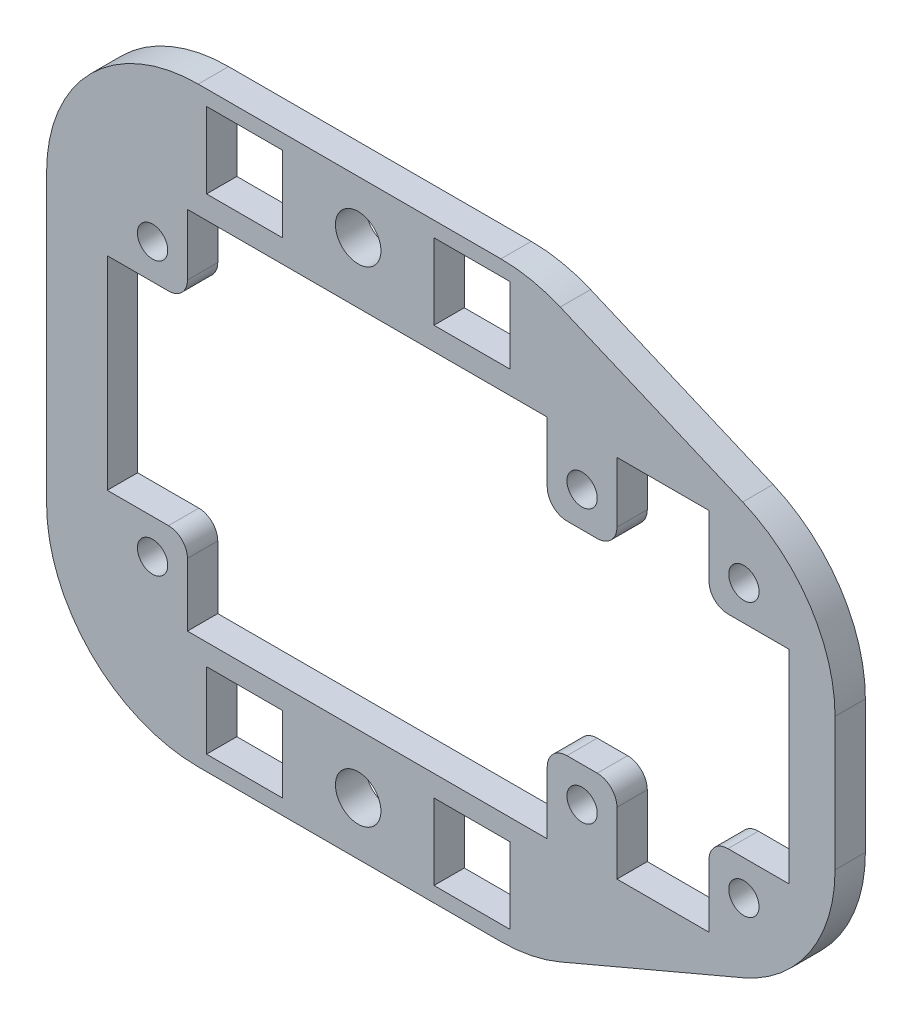
SolidWorks part; units mm, degrees
ref_plane "Plan de face" through (0, 0, 0) normal (0, 0, 1) x (1, 0, 0)
ref_plane "Plan de dessus" through (0, 0, 0) normal (0, 1, 0) x (1, 0, 0)
ref_plane "Plan de droite" through (0, 0, 0) normal (1, 0, 0) x (0, 0, -1)
sketch "Esquisse1" plane through (0, 0, 0) normal (0, 0, 1) x (1, 0, 0)
  line L0 (-4, 19.5) -> (48, 19.5) construction
  line L1 (48, 19.5) -> (48, -19.5) construction
  line L2 (48, -19.5) -> (-4, -19.5) construction
  line L3 (-4, -19.5) -> (-4, 19.5)
  line L4 (0, 0) -> (44.9752, 0) construction
  line L5 (-4, 19.5) -> (28, 19.5)
  line L6 (28, 19.5) -> (48, 11)
  line L7 (48, 11) -> (48, -11)
  line L8 (48, -11) -> (28, -19.5)
  line L9 (28, -19.5) -> (-4, -19.5)
  point P0 (0, 0)
  line B0 (28.5158, -12.1) -> (5.9876, -12.1) construction
  line B1 (0.2864, -6.7) -> (0.2984, -6.7)
  line B2 (5.2876, -7.95) -> (5.2876, -11.5) construction
  line B3 (0.2984, -6.7) -> (4.0376, -6.7) construction
  line B4 (0, -8) -> (0, 8) construction
  line B5 (44.6876, -6.7) -> (40.9376, -6.7) construction
  line B6 (39.6876, -7.95) -> (39.6876, -11.7) construction
  line B7 (44.9752, 8) -> (44.9752, -8) construction
  line B8 (4.0376, 6.7) -> (0, 6.7)
  line B9 (3.9876, 11.9876) -> (40.9876, 11.9876) construction
  line B10 (0, 6.7) -> (0, -6.7)
  line B11 (0, -6.7) -> (4.0376, -6.7)
  line B12 (39.6876, 7.95) -> (39.6876, 11.6999) construction
  line B13 (44.6876, 6.7) -> (40.9376, 6.7) construction
  line B14 (5.2876, -7.95) -> (5.2876, -12.1)
  line B15 (5.2876, -12.1) -> (29.0158, -12.1)
  line B16 (29.0158, -12.1) -> (29.0158, -8)
  line B17 (33.6158, -8) -> (33.6158, -12.1)
  line B18 (33.6158, -12.1) -> (39.6876, -12.1)
  line B19 (39.6876, -12.1) -> (39.6876, -7.95)
  line B20 (40.9376, -6.7) -> (44.9752, -6.7)
  line B21 (44.9752, -6.7) -> (44.9752, 6.7)
  line B22 (44.9752, 6.7) -> (40.9376, 6.7)
  line B23 (39.6876, 7.95) -> (39.6876, 11.9876)
  line B24 (39.6876, 11.9876) -> (33.6158, 11.9876)
  line B25 (33.6158, 11.9876) -> (33.6158, 8)
  line B26 (29.0158, 8) -> (29.0158, 11.9876)
  line B27 (29.0158, 11.9876) -> (5.2876, 11.9876)
  line B28 (5.2876, 11.9876) -> (5.2876, 7.95)
  line B29 (0.2984, 6.7) -> (0.2864, 6.6999)
  line B30 (4.0376, 6.7) -> (0.2984, 6.7) construction
  line B31 (5.2876, 11.4999) -> (5.2876, 7.95) construction
  line B32 (29.0158, 8) -> (29.0158, 11.6999) construction
  line B33 (33.6158, 11.6999) -> (33.6158, 8) construction
  line B34 (32.3158, 6.7) -> (30.3158, 6.7)
  line B35 (33.6158, -8) -> (33.6158, -11.7) construction
  line B36 (30.3158, -6.7) -> (32.3158, -6.7)
  line B37 (29.0158, -11.7) -> (29.0158, -8) construction
  arc B38 (5.2876, -7.95) -> (4.0376, -6.7) centre (4.0376, -7.95) ccw
  arc B39 (40.9376, -6.7) -> (39.6876, -7.95) centre (40.9376, -7.95) ccw
  arc B40 (31.3158, 10) -> (31.3158, 8) centre (31.3158, 9) ccw
  arc B41 (31.3158, 8) -> (31.3158, 10) centre (31.3158, 9) ccw
  arc B42 (39.6876, 7.95) -> (40.9376, 6.7) centre (40.9376, 7.95) ccw
  arc B43 (42.9876, 9) -> (40.9876, 9) centre (41.9876, 9) ccw
  arc B44 (40.9876, 9) -> (42.9876, 9) centre (41.9876, 9) ccw
  arc B45 (42.9876, -9) -> (40.9876, -9) centre (41.9876, -9) ccw
  arc B46 (40.9876, -9) -> (42.9876, -9) centre (41.9876, -9) ccw
  arc B47 (4.0376, 6.7) -> (5.2876, 7.95) centre (4.0376, 7.95) ccw
  arc B48 (31.3158, -8) -> (31.3158, -10) centre (31.3158, -9) ccw
  arc B49 (31.3158, -10) -> (31.3158, -8) centre (31.3158, -9) ccw
  arc B50 (32.3158, 6.7) -> (33.6158, 8) centre (32.3158, 8) ccw
  arc B51 (29.0158, 8) -> (30.3158, 6.7) centre (30.3158, 8) ccw
  arc B52 (33.6158, -8) -> (32.3158, -6.7) centre (32.3158, -8) ccw
  arc B53 (30.3158, -6.7) -> (29.0158, -8) centre (30.3158, -8) ccw
  arc B54 (1.9876, -9) -> (3.9876, -9) centre (2.9876, -9) ccw
  arc B55 (3.9876, -9) -> (1.9876, -9) centre (2.9876, -9) ccw
  arc B56 (1.9876, 9) -> (3.9876, 9) centre (2.9876, 9) ccw
  arc B57 (3.9876, 9) -> (1.9876, 9) centre (2.9876, 9) ccw
  line B58 (11.5481, 16) -> (21.5481, 16) construction
  line B59 (11.5481, 18.5) -> (6.5481, 18.5)
  line B60 (11.5481, 18.5) -> (11.5481, 13.5)
  line B61 (11.5481, 13.5) -> (6.5481, 13.5)
  line B62 (6.5481, 18.5) -> (6.5481, 13.5)
  line B63 (21.5481, 18.5) -> (26.5481, 18.5)
  line B64 (21.5481, 18.5) -> (21.5481, 13.5)
  line B65 (21.5481, 13.5) -> (26.5481, 13.5)
  line B66 (26.5481, 18.5) -> (26.5481, 13.5)
  line B67 (16.5481, 16) -> (16.5481, 22.9724) construction
  circle B68 centre (16.5481, 16) radius 1.5
  line B69 (11.5481, -16) -> (21.5481, -16) construction
  line B70 (11.5481, -18.5) -> (6.5481, -18.5)
  line B71 (11.5481, -18.5) -> (11.5481, -13.5)
  line B72 (11.5481, -13.5) -> (6.5481, -13.5)
  line B73 (6.5481, -18.5) -> (6.5481, -13.5)
  line B74 (21.5481, -18.5) -> (26.5481, -18.5)
  line B75 (21.5481, -18.5) -> (21.5481, -13.5)
  line B76 (21.5481, -13.5) -> (26.5481, -13.5)
  line B77 (26.5481, -18.5) -> (26.5481, -13.5)
  line B78 (16.5481, -16) -> (16.5481, -22.9724) construction
  circle B79 centre (16.5481, -16) radius 1.5
  dimension "D1" = 39
  dimension "D2" = 52
  dimension "D3" = 4
  dimension "D4" = 20
  dimension "D6" = 32
  dimension "D7" = 22
sketch_block_instance "Block1-1"
sketch_block "Block1"
sketch_block_instance "Trou M3 plots 5mm-1"
sketch_block "Trou M3 plots 5mm" parameters "D2"=3, "D1"=5, "D3"=5, "D4"=10
sketch_block_instance "Trou M3 plots 5mm-3"
extrude "Boss.-Extru.1" add sketch "Esquisse1" along normal blind 2
fillet "Fillet1" radius 10 6 edges at (28, 19.5, 1) (-4, 19.5, 1) (-4, -19.5, 1) (28, -19.5, 1) (48, -11, 1) (48, 11, 1)
